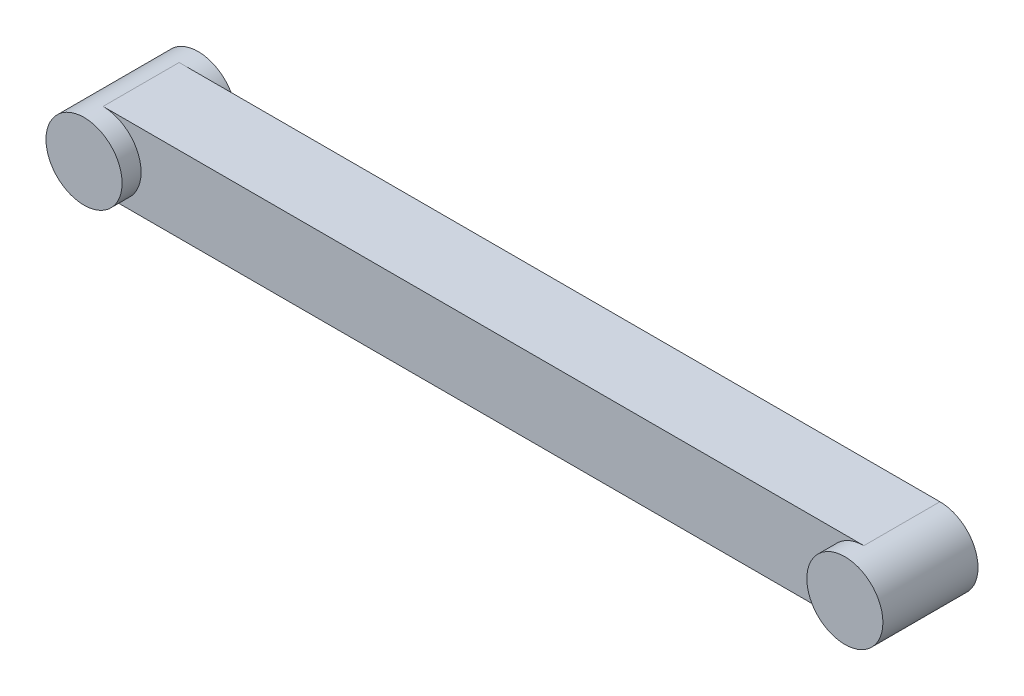
SolidWorks part; units mm, degrees
ref_plane "Front Plane" through (0, 0, 0) normal (0, 0, 1) x (1, 0, 0)
ref_plane "Top Plane" through (0, 0, 0) normal (0, 1, 0) x (1, 0, 0)
ref_plane "Right Plane" through (0, 0, 0) normal (1, 0, 0) x (0, 0, -1)
sketch "Sketch1" plane through (0, 0, 0) normal (0, 0, 1) x (1, 0, 0)
  line L0 (-46.1354, 14.6475) -> (153.8646, 14.6475)
  line L1 (153.8646, -5.3525) -> (-46.1354, -5.3525)
  arc A0 (153.8646, 14.6475) -> (163.8646, 4.6475) centre (153.8646, 4.6475) cw
  arc A1 (163.8646, 4.6475) -> (153.8646, -5.3525) centre (153.8646, 4.6475) cw
  arc A2 (-46.1354, 14.6475) -> (-56.1354, 4.6475) centre (-46.1354, 4.6475) ccw
  arc A3 (-56.1354, 4.6475) -> (-46.1354, -5.3525) centre (-46.1354, 4.6475) ccw
extrude "Boss-Extrude1" add sketch "Sketch1" along normal blind 20
sketch "Sketch2" plane through (0, 0, 20) normal (0, 0, 1) x (1, 0, 0)
  circle A0 centre (-46.1354, 4.6475) radius 10
extrude "Boss-Extrude2" add sketch "Sketch2" along normal blind 5
sketch "Sketch3" plane through (0, 0, 0) normal (0, 0, -1) x (-1, 0, 0)
  circle A0 centre (46.1354, 4.6475) radius 10
extrude "Boss-Extrude3" add sketch "Sketch3" along normal blind 5
sketch "Sketch4" plane through (0, 0, 20) normal (0, 0, 1) x (1, 0, 0)
  circle A0 centre (153.8646, 4.6475) radius 10
extrude "Boss-Extrude4" add sketch "Sketch4" along normal blind 5
